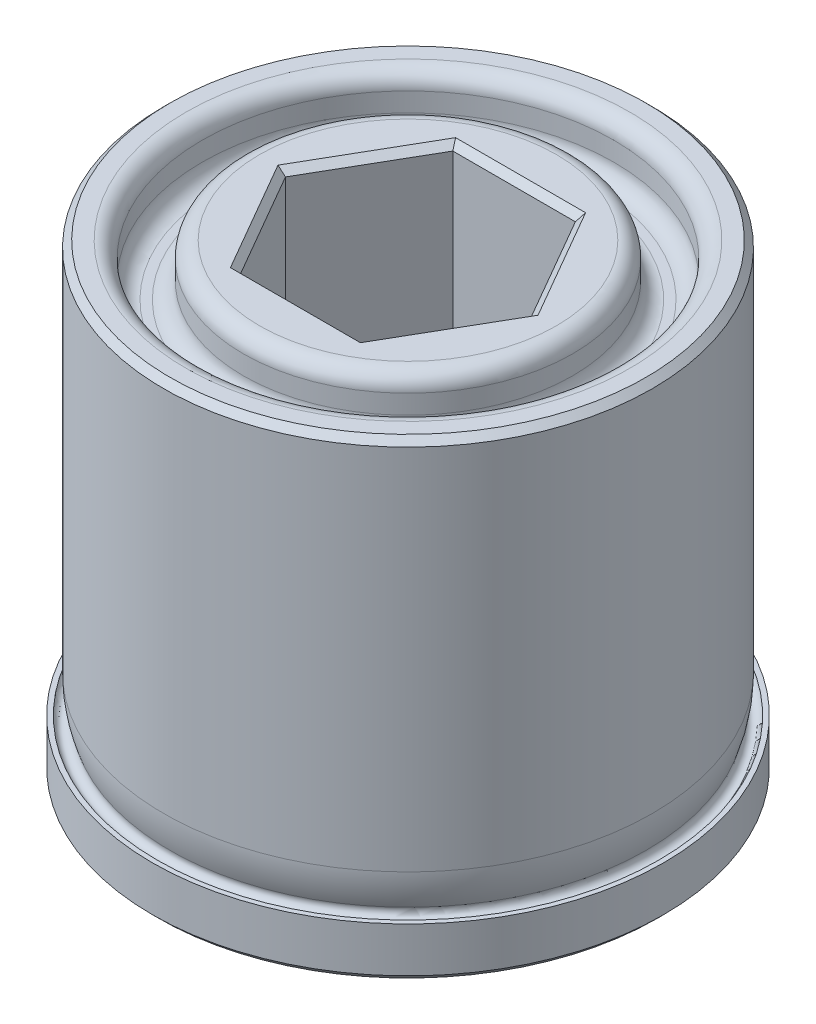
SolidWorks part; units mm, degrees
ref_plane "Front Plane" through (0, 0, 0) normal (0, 0, 1) x (1, 0, 0)
ref_plane "Top Plane" through (0, 0, 0) normal (0, 1, 0) x (1, 0, 0)
ref_plane "Right Plane" through (0, 0, 0) normal (1, 0, 0) x (0, 0, -1)
sketch "Sketch4" plane through (0, 0, 0) normal (0, 0, 1) x (1, 0, 0)
  line L2 (0, 0) -> (0, 25.4)
  line L3 (0, 25.4) -> (15.0813, 25.4)
  line L4 (15.0813, 0.4) -> (15.0813, 25.4)
  line L5 (15.4813, 0) -> (15.775, 0)
  line L6 (0, 0) -> (0, -3.175)
  line L7 (0, -3.175) -> (15.775, -3.175)
  line L8 (15.775, 0) -> (15.775, -3.175)
  arc A0 (15.0813, 0.4) -> (15.4813, 0) centre (15.0813, 0) ccw
  dimension "D5" = 0.4
  dimension "D1" = 3.175
  dimension "D2" = 15.0813
  dimension "D3" = 15.775
  dimension "D4" = 25.4
revolve "Revolve1" add sketch "Sketch4" angle 360 about L2
chamfer "Chamfer1" distance 0.4 angle 45 1 edges at (15.0813, 25.4, 0)
sketch "Sketch5" plane through (0, 25.4, 0) normal (0, 1, 0) x (1, 0, 0)
  line L1 (7.5633, 0) -> (3.7816, 6.55)
  line L2 (3.7816, 6.55) -> (-3.7816, 6.55)
  line L3 (-3.7816, 6.55) -> (-7.5633, 0)
  line L4 (-7.5633, 0) -> (-3.7816, -6.55)
  line L5 (-3.7816, -6.55) -> (3.7816, -6.55)
  line L6 (3.7816, -6.55) -> (7.5633, 0)
  circle A0 centre (0, 0) radius 6.55 construction
  dimension "D1" = 13.1
extrude "Cut-Extrude1" cut sketch "Sketch5" against normal blind 38.1
chamfer "Chamfer2" distance 0.4 angle 45 12 edges at (5.6725, -3.175, 3.275) (0, -3.175, 6.55) (-5.6725, -3.175, 3.275) (-5.6725, -3.175, -3.275) (5.6725, -3.175, -3.275) (0, -3.175, -6.55) (5.6725, 25.4, -3.275) (5.6725, 25.4, 3.275) (0, 25.4, 6.55) (-5.6725, 25.4, 3.275) (-5.6725, 25.4, -3.275) (0, 25.4, -6.55)
chamfer "Chamfer3" distance 0.4 angle 45 1 edges at (15.775, -3.175, 0)
sketch "Sketch6" plane through (0, 25.4, 0) normal (0, 1, 0) x (1, 0, 0)
  circle A0 centre (0, 0) radius 12.7
  circle A1 centre (0, 0) radius 10.16
  dimension "D1" = 2.54
extrude "Cut-Extrude2" cut sketch "Sketch6" against normal blind 3.175
fillet "Fillet2" radius 1 4 edges at (-12.7, 25.4, 0) (-10.16, 25.4, 0) (-10.16, 22.225, 0) (-12.7, 22.225, 0)
fillet "Fillet7" radius 6.35 1 edges at (15.0813, 0.4, 0)
